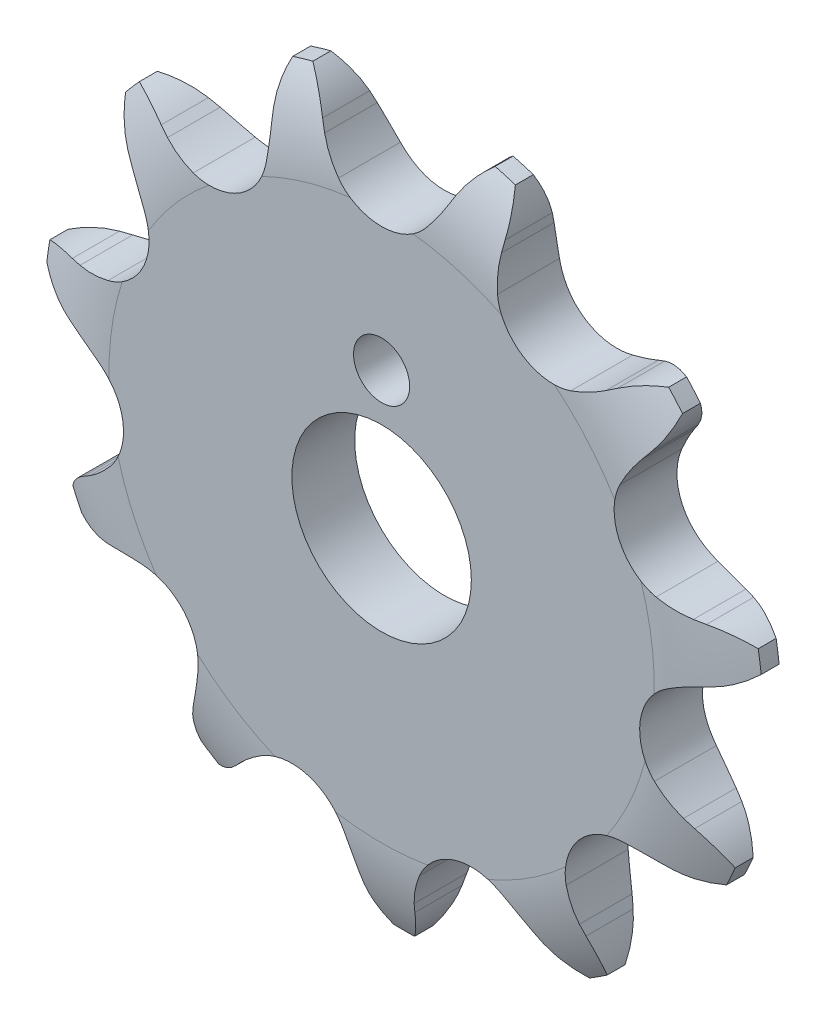
SolidWorks part; units mm, degrees
ref_plane "Front Plane" through (0, 0, 0) normal (0, 0, 1) x (1, 0, 0)
ref_plane "Top Plane" through (0, 0, 0) normal (0, 1, 0) x (1, 0, 0)
ref_plane "Right Plane" through (0, 0, 0) normal (1, 0, 0) x (0, 0, -1)
sketch "Sketch0" plane through (0, 0, 0) normal (0, 0, 1) x (1, 0, 0)
  line L0 (4, -13.6227) -> (0, 0) construction
  line L1 (0, 0) -> (10.73, -9.2976) construction
  line L2 (0, 0) -> (-4, -13.6227) construction
  line L3 (4, -13.6227) -> (10.73, -9.2976) construction
  line L4 (4, -13.6227) -> (-4, -13.6227) construction
  line L5 (6.8518, -12.7617) -> (6.5301, -12.4276)
  line L6 (4, -13.6227) -> (0, -14.7973) construction
  line L7 (1.1354, -14.4402) -> (1.2253, -13.9852)
  line L8 (0, -13.6227) -> (0, -16.0227) construction
  line L9 (5.3959, -11.4881) -> (1.8108, -16.9705) construction
  line L10 (0, 0) -> (0, -13.6227) construction
  line L11 (6.5301, -12.4276) -> (1.8108, -16.9705) construction
  line L12 (0, -16.0227) -> (0, -16.5841) construction
  line L13 (9.8888, -9.8383) -> (6.8518, -12.7617) construction
  circle A0 centre (0, 0) radius 16.0227 construction
  circle A1 centre (0, 0) radius 14.1979 construction
  arc A2 (-3.9066, -17.7395) -> (12.8771, -12.8114) centre (0, 0) ccw
  circle A3 centre (0, 0) radius 16.5841 construction
  circle A4 centre (4, -13.6227) radius 2.5 construction
  arc A7 (5.3959, -11.4881) -> (1.6716, -12.5816) centre (4, -13.6227) ccw
  circle A8 centre (4, -13.6227) radius 2.5506 construction
  arc A9 (6.8518, -12.7617) -> (12.8771, -12.8114) centre (9.8888, -9.8383) ccw
  arc A10 (6.5301, -12.4276) -> (5.3959, -11.4881) centre (1.8108, -16.9705) ccw
  arc A11 (1.1354, -14.4402) -> (-3.9066, -17.7395) centre (-3, -13.6227) cw
  arc A12 (1.2253, -13.9852) -> (1.6716, -12.5816) centre (7.6516, -15.2555) cw
  dimension "D1" = 2.5506
  dimension "R" = 2.5506
sketch "Sketch1" plane through (0, 0, 0) normal (1, 0, 0) x (0, 0, -1)
  line L0 (1.4, 0) -> (-1.4, 0)
  line L1 (-1.4, 0) -> (-1.4, 12.1498)
  line L2 (-1.4, 14.1979) -> (0, 14.1979) construction
  line L3 (-0.4, 16.0227) -> (0.4, 16.0227)
  line L5 (1.4, 12.1498) -> (1.4, 0)
  line L7 (0, 16.0227) -> (0, 0) construction
  line L8 (-1.4, 12.1498) -> (1.4, 12.1498) construction
  line L9 (0, 16.0227) -> (0, -16.0227) construction
  line L10 (-1.4, 12.1498) -> (-1.4, 16.0227) construction
  line L11 (-1.4, 16.0227) -> (-0.4, 16.0227) construction
  line L12 (0.4, 16.0227) -> (1.4, 16.0227) construction
  line L13 (1.4, 16.0227) -> (1.4, 12.1498) construction
  line L14 (0, 0) -> (-6.4008, 0) construction
  line L15 (-1.4, 14.1979) -> (-1.4, 8.8979) construction
  line L22 (1.4, 0) -> (-11.6, 0) construction
  line L24 (-1.4, 0) -> (-1.4, 8.8979) construction
  arc A0 (-0.4, 16.0227) -> (-1.4, 12.1498) centre (6.6, 12.1498) ccw
  arc A1 (0.4, 16.0227) -> (1.4, 12.1498) centre (-6.6, 12.1498) cw
  dimension "R" = 8
revolve "Revolve1" add sketch "Sketch1" angle 360 mid plane about L0
extrude "Cut-Extrude1" cut sketch "Sketch0" against normal through all and the other way through all
pattern_circular "CirPattern1" count 11 over 360 about axis through (0, 0, 0) along (0, 0, 1) of "Cut-Extrude1"
sketch "Sketch2" plane through (0, 0, 0) normal (0, 0, 1) x (1, 0, 0)
  circle A0 centre (0, 0) radius 4 construction
  circle A1 centre (0, 0) radius 9
  circle A2 centre (0, 0) radius 16.025 construction
  dimension "Bore" = 8
  dimension "Hub Dia." = 18
  dimension "OD" = 32.05
extrude "Boss-Extrude1" add sketch "Sketch2" along normal up to vertex (11.6 mm away) from surface at 1.4 starting at face at (0, 0, 1.4)
sketch "Sketch3" plane through (0, 0, 0) normal (0, 0, 1) x (1, 0, 0)
  circle A0 centre (0, 0) radius 4 construction
  circle A1 centre (0, 0) radius 4
extrude "Cut-Extrude2" cut sketch "Sketch3" along normal through all and the other way through all
sketch "Sketch4" plane through (0, 0, 0) normal (1, 0, 0) x (0, 0, -1)
  line L0 (-11.6, 9) -> (-11.6, 8.5)
  line L1 (-1.4, 16.0227) -> (-3.5, 16.0227)
  line L2 (-1.4, 16.0227) -> (-1.4, 8.8979)
  line L3 (-1.4, 8.8979) -> (-3.5, 8.8979)
  line L4 (-3.5, 16.0227) -> (-3.5, 8.8979)
  line L9 (-11.6, 8.5) -> (-11.1, 9)
  line L10 (-11.1, 9) -> (-11.6, 9)
  dimension "C" = 0.5
  dimension "D3" = 2.1
revolve "Cut-Revolve1" cut sketch "Sketch4" angle 360 mid plane about L22
sketch "Sketch5" plane through (0, 0, 0) normal (0, 0, 1) x (1, 0, 0)
  circle A0 centre (0, 0) radius 16.025 construction
  circle A1 centre (0, 0) radius 16.025
extrude "Cut-Extrude3" [suppressed] cut sketch "Sketch5" against normal through all and the other way through all flip side to cut
sketch "Sketch6" plane through (0, 0, 1.4) normal (0, 0, 1) x (1, 0, 0)
  circle A0 centre (0, 0) radius 10
  dimension "D1" = 20
extrude "Cut-Extrude5" cut sketch "Sketch6" along normal blind 20
sketch "Sketch7" plane through (0, 0, 1.4) normal (0, 0, 1) x (1, 0, 0)
  circle A0 centre (0, 0) radius 6.1 construction
  circle A1 centre (0, 6.1) radius 1.25
  dimension "D1" = 12.2
  dimension "D2" = 2.5
extrude "Cut-Extrude6" cut sketch "Sketch7" against normal up to surface (2.8 mm away) up to face at (0, 0, -1.4)
equation "\"360/N@Sketch0\" = 360/\"Teeth@CirPattern1\""
equation "\"Ds@Sketch0\" = 1.005 * \"Dr@Sketch0\" + ( 0.003 * 25.4 ) "
equation "\"R@Sketch0\" = 1/2 * \"Ds@Sketch0\""
equation "\"A@Sketch0\" = 35 +  ( 60 / \"Teeth@CirPattern1\" ) "
equation "\"B@Sketch0\" = 18 -  ( 56 / \"Teeth@CirPattern1\" )"
equation "\"ac@Sketch0\" = 0.8 * \"Dr@Sketch0\""
equation "\"ab@Sketch0\" = 1.4 * \"Dr@Sketch0\""
equation "\"J@Sketch0\" = 0.3 * \"Pitch@Sketch0\""
equation "\"D3@Sketch4\" = \"t@Sketch1\" * 3 / 4"
